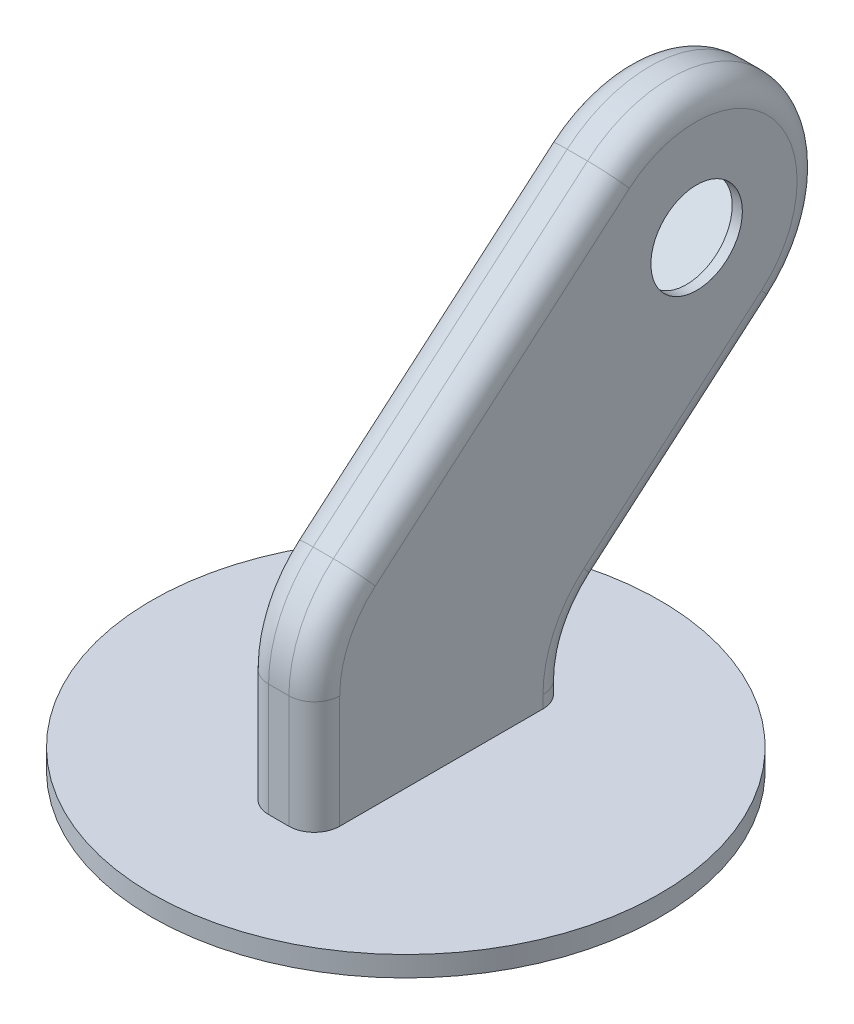
SolidWorks part; units mm, degrees
material "ABS"
ref_plane "Front Plane" through (0, 0, 0) normal (0, 0, 1) x (1, 0, 0)
ref_plane "Top Plane" through (0, 0, 0) normal (0, 1, 0) x (1, 0, 0)
ref_plane "Right Plane" through (0, 0, 0) normal (1, 0, 0) x (0, 0, -1)
sketch "Sketch2" plane through (0, 0, 0) normal (0, 1, 0) x (1, 0, 0)
  circle A0 centre (0, 0) radius 50
  dimension "D1" = 100
extrude "Boss-Extrude1" add sketch "Sketch2" along normal blind 4
sketch "Sketch4" plane through (0, 0, 0) normal (0, -1, 0) x (1, 0, 0)
  circle A0 centre (0, 6) radius 1.5
  circle A1 centre (0, -6) radius 1.5
  dimension "D1" = 3
  dimension "D2" = 3
  dimension "D3" = 12
  dimension "D4" = 6
sketch "Sketch5" plane through (0, 0, 0) normal (0, -1, 0) x (1, 0, 0)
  circle A0 centre (0, 0) radius 2.5
  dimension "D1" = 5
ref_plane "Plane1" through (7, 0, 0) normal (1, 0, 0) x (0, 0, -1)
sketch "Sketch7" plane through (7, 0, 0) normal (1, 0, 0) x (0, 0, -1)
  line L0 (25, 6.4288) -> (25, 4)
  line L5 (50, 4) -> (-50, 4) construction
  line L6 (-16.25, 45.2315) -> (33.75, 87.9984)
  line L7 (-25, 4) -> (25, 4)
  line L11 (-25, 4) -> (-25, 26.2331)
  line L12 (31.3, 20.1076) -> (66.25, 50.0016)
  line L13 (66.25, 50.0016) -> (33.75, 87.9984) construction
  line L14 (68.9984, 85.25) -> (-82.8307, -44.6151) construction
  arc A5 (31.3, 20.1076) -> (25, 6.4288) centre (43, 6.4288) ccw
  arc A6 (-16.25, 45.2315) -> (-25, 26.2331) centre (0, 26.2331) ccw
  arc A7 (33.75, 87.9984) -> (66.25, 50.0016) centre (50, 69) cw
  point P9 (-25.9934, 4)
  dimension "D1" = 25
  dimension "D4" = 50
  dimension "D2" = 50
  dimension "D3" = 25
  dimension "D6" = 65
  dimension "D5" = 100
extrude "Boss-Extrude2" add sketch "Sketch7" against normal blind 14
ref_plane "Plane2" through (5, 0, 0) normal (1, 0, 0) x (0, 0, -1)
sketch "Sketch8" plane through (5, 0, 0) normal (1, 0, 0) x (0, 0, -1)
  line L1 (20.225, 57.3493) -> (51.3823, 83.9993)
  line L2 (20.225, 57.3493) -> (33.875, 41.3907)
  line L3 (33.875, 41.3907) -> (65.0323, 68.0407)
  line L4 (51.3823, 83.9993) -> (65.0323, 68.0407)
  line L9 (-16.25, 45.2315) -> (33.75, 87.9984) construction
  line L12 (31.3, 20.1076) -> (66.25, 50.0016) construction
  dimension "D1" = 41
  dimension "D2" = 21
  dimension "D3" = 90
  dimension "D4" = 14.5
  dimension "D5" = 90
  dimension "D9" = 10.8
extrude "Cut-Extrude5" cut sketch "Sketch8" against normal up to next
sketch "Sketch30" plane through (0, 0, 0) normal (0, -1, 0) x (1, 0, 0)
  circle A0 centre (0, 0) radius 20
  dimension "D1" = 40
extrude "Boss-Extrude12" add sketch "Sketch30" along normal blind 5 contours A0
extrude "Cut-Extrude18" cut sketch "Sketch5" along normal blind 5 contours A0
extrude "Cut-Extrude19" cut sketch "Sketch4" along normal blind 5
sketch "Sketch9" plane through (-7, 0, 0) normal (-1, 0, 0) x (0, 0, 1)
  line L0 (-51.3823, 83.9993) -> (-65.0323, 68.0407) construction
  line L1 (-33.875, 41.3907) -> (-20.225, 57.3493) construction
  line L2 (-65.0323, 68.0407) -> (-33.875, 41.3907) construction
  line L3 (-20.225, 57.3493) -> (-51.3823, 83.9993) construction
  circle A1 centre (-65.029, 75.2753) radius 2
  circle A6 centre (-20.2283, 50.1147) radius 2
  circle A7 centre (-26.7283, 42.5153) radius 2
  circle A8 centre (-58.529, 82.8747) radius 2
  dimension "D5" = 4.7
  dimension "D6" = 5.5
  dimension "D7" = 5.5
  dimension "D8" = 4
  dimension "D9" = 4
  dimension "D10" = 10
  dimension "D12" = 4.7
  dimension "D13" = 4.7
  dimension "D2" = 4
  dimension "D3" = 4
  dimension "D4" = 10
  dimension "D11" = 5.5
extrude "Cut-Extrude6" cut sketch "Sketch9" against normal blind 7.5
sketch "Sketch27" plane through (0, 4, 0) normal (0, 1, 0) x (1, 0, 0)
  line L1 (9, -9) -> (25, -9)
  line L2 (9, -9) -> (9, -15)
  line L3 (9, -15) -> (25, -15)
  line L4 (25, -9) -> (25, -15)
  line L5 (-7, -25) -> (7, -25) construction
  line L6 (7, -25) -> (7, 25) construction
  dimension "D1" = 10
  dimension "D2" = 6
  dimension "D3" = 16
  dimension "D4" = 2
extrude "Boss-Extrude11" [suppressed] add sketch "Sketch27" along normal blind 12
fillet "Fillet6" [suppressed] radius 3
sketch "Sketch28" [suppressed] plane through (0, 0, 24.5496) normal (0, 0, 1) x (1, 0, 0)
  line L8 (10, 12) -> (2, 12)
  line L9 (2, 12) -> (2, 8)
  line L10 (2, 8) -> (10, 8)
  line L11 (10, 8) -> (10, 12)
  line L12 (10, 12) -> (2, 12)
  line L13 (2, 12) -> (2, 8)
  line L14 (2, 8) -> (10, 8)
  line L15 (10, 8) -> (10, 12)
  dimension "D1" = 4
extrude "Cut-Extrude16" [suppressed] cut sketch "Sketch28" against normal up to next
fillet "Fillet7" radius 5 14 edges at (7, 15.1166, 25) (-7, 15.1166, 25) (7, 36.6914, 22.7074) (-7, 36.6914, 22.7074) (7, 5.2144, -25) (-7, 5.2144, -25) (7, 13.9587, -26.6507) (-7, 13.9587, -26.6507) (7, 35.0546, -48.775) (-7, 35.0546, -48.775) (7, 85.25, -68.9984) (-7, 85.25, -68.9984) (7, 66.6149, -8.75) (-7, 66.6149, -8.75)
sketch "Sketch31" plane through (-7, 0, 0) normal (-1, 0, 0) x (0, 0, 1)
  line L0 (-14.5255, 52.4743) -> (-28.1755, 36.5157)
  line L1 (-28.1755, 36.5157) -> (-70.7318, 72.9157)
  line L2 (-70.7318, 72.9157) -> (-57.0818, 88.8743)
  line L3 (-57.0818, 88.8743) -> (-14.5255, 52.4743)
  line L4 (-33.875, 41.3907) -> (-20.225, 57.3493) construction
  line L5 (-20.225, 57.3493) -> (-51.3823, 83.9993) construction
  line L6 (-65.0323, 68.0407) -> (-33.875, 41.3907) construction
  line L7 (-51.3823, 83.9993) -> (-65.0323, 68.0407) construction
  dimension "D1" = 7.5
  dimension "D2" = 7.5
  dimension "D3" = 0
  dimension "D4" = 0
extrude "Cut-Extrude20" cut sketch "Sketch31" against normal blind 1.5
sketch "Sketch32" plane through (7, 0, 0) normal (1, 0, 0) x (0, 0, -1)
  circle A0 centre (50.228, 69.195) radius 9
  dimension "D1" = 18
extrude "Cut-Extrude21" cut sketch "Sketch32" against normal blind 10 contours A0
